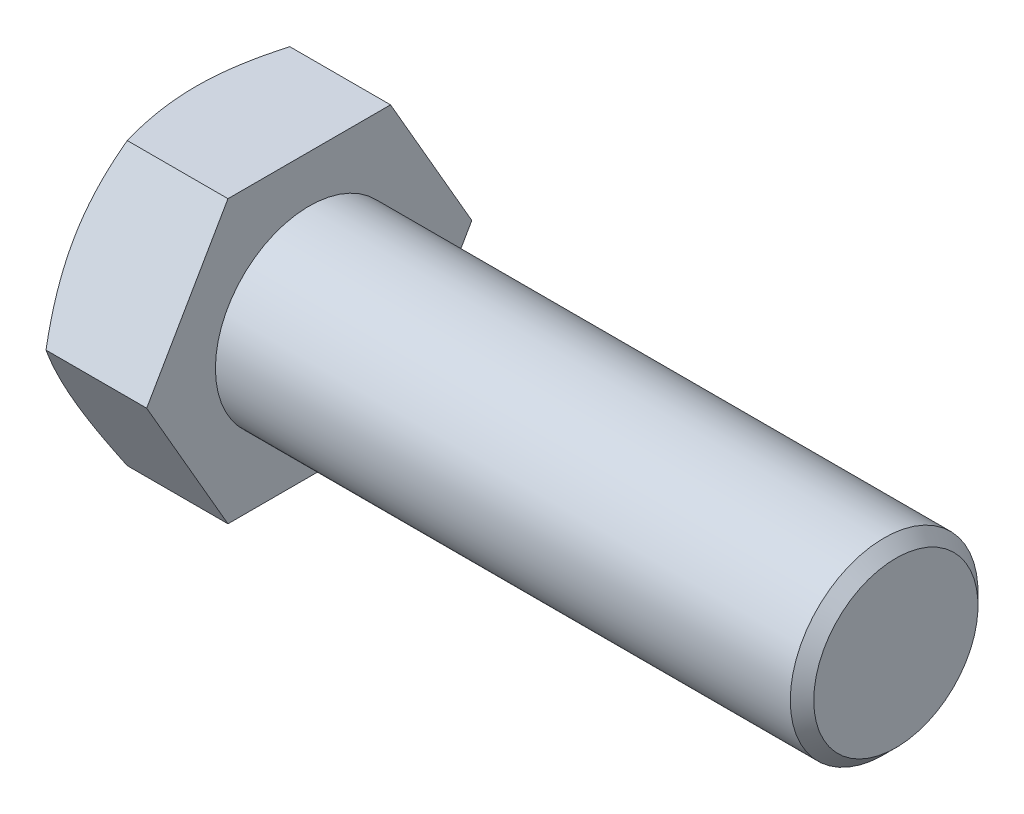
SolidWorks part; units mm, degrees
ref_plane "Спереди" through (0, 0, 0) normal (0, 0, 1) x (1, 0, 0)
ref_plane "Сверху" through (0, 0, 0) normal (0, 1, 0) x (1, 0, 0)
ref_plane "Справа" through (0, 0, 0) normal (1, 0, 0) x (0, 0, -1)
sketch "Эскиз1" plane through (0, 0, 0) normal (0, 0, 1) x (1, 0, 0)
  line L0 (0, 0) -> (30, 0) construction
  line L1 (0, 0) -> (0, 5.7)
  line L2 (0, 5.7) -> (0.7101, 6.93)
  line L3 (0.7101, 6.93) -> (5, 6.93)
  line L4 (5, 6.93) -> (5, 4)
  line L5 (5, 4) -> (30, 4)
  line L6 (30, 4) -> (30, 0)
  line L7 (0, 5.7) -> (0, 11.3746) construction
  line L8 (0, 0) -> (30, 0)
  dimension "D1" = 11.4
  dimension "d" = 8
  dimension "k" = 5
  dimension "al" = 30
  dimension "e" = 13.86
  dimension "l" = 25
revolve "Повернуть1" add sketch "Эскиз1" angle 360 about L8
sketch "Эскиз2" plane through (0, 0, 0) normal (1, 0, 0) x (0, 0, -1)
  line L1 (6.9282, 0) -> (3.4641, 6)
  line L2 (3.4641, 6) -> (-3.4641, 6)
  line L3 (-3.4641, 6) -> (-6.9282, 0)
  line L4 (-6.9282, 0) -> (-3.4641, -6)
  line L5 (-3.4641, -6) -> (3.4641, -6)
  line L6 (3.4641, -6) -> (6.9282, 0)
  circle A0 centre (0, 0) radius 6 construction
  point P1 (0, 0)
  dimension "S" = 12
extrude "Вырез-Вытянуть1" cut sketch "Эскиз2" along normal through all flip side to cut
chamfer "Фаска1" distance 0.5 angle 45 1 edges at (30, 0, 4)
